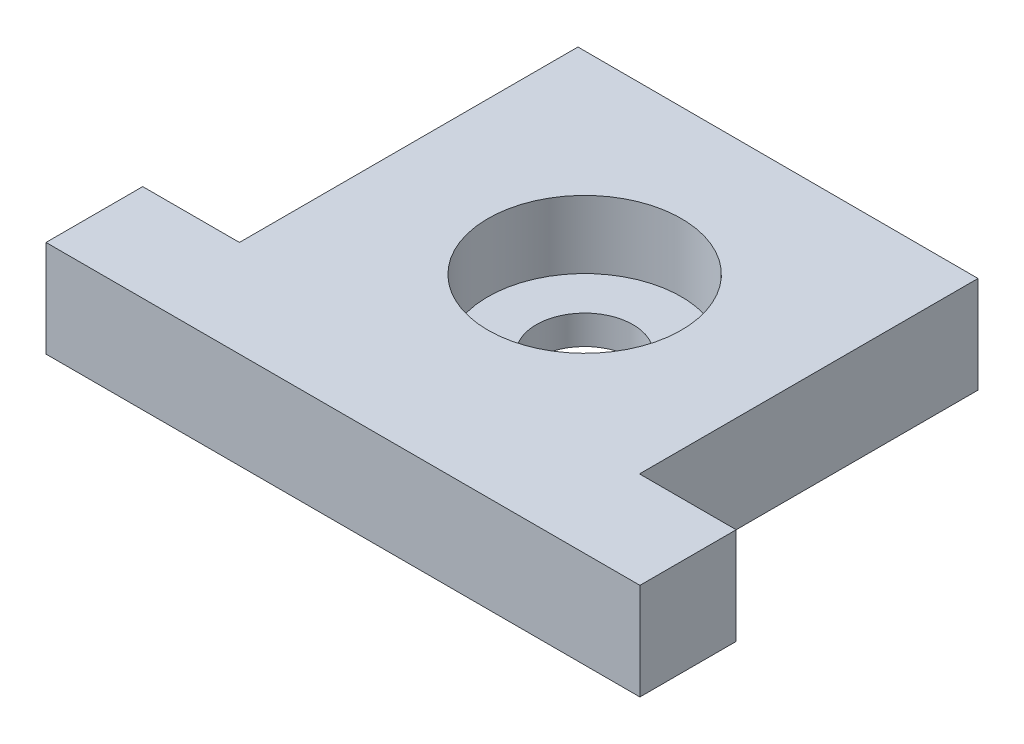
SolidWorks part; units mm, degrees
ref_plane "Front Plane" through (0, 0, 0) normal (0, 0, 1) x (1, 0, 0)
ref_plane "Top Plane" through (0, 0, 0) normal (0, 1, 0) x (1, 0, 0)
ref_plane "Right Plane" through (0, 0, 0) normal (1, 0, 0) x (0, 0, -1)
sketch "Sketch1" plane through (0, 0, 0) normal (0, 1, 0) x (1, 0, 0)
  line L0 (-30.704, 0) -> (30.704, 0)
  line L1 (-30.704, 0) -> (-30.704, 10)
  line L2 (30.704, 0) -> (30.704, 9.955)
  line L3 (-30.704, 10) -> (-20.704, 10)
  line L4 (30.704, 9.955) -> (20.704, 9.955)
  line L5 (-20.704, 10) -> (-20.704, 45)
  line L6 (20.704, 9.955) -> (20.704, 44.955)
  line L7 (-20.704, 45) -> (20.704, 44.955)
  line L8 (20.704, 44.955) -> (20.6896, 45.0291)
  point P4 (0, 0)
extrude "Boss-Extrude1" add sketch "Sketch1" along normal blind 10 contours L7 L5 L3 L1 L0 L2 L4 L6
sketch "Sketch2" plane through (0, 10, 0) normal (0, 1, 0) x (1, 0, 0)
  line L0 (-30.704, 0) -> (30.704, 0) construction
  circle A0 centre (0, 24.9888) radius 10
  point P0 (0, 0)
  point P8 (0, 22.4888)
  point P9 (0, 22.4888)
  dimension "D1" = 24.9888
extrude "Cut-Extrude2" cut sketch "Sketch2" against normal blind 7
sketch "Sketch5" plane through (0, 3, 0) normal (0, 1, 0) x (1, 0, 0)
  circle A0 centre (0, 24.9888) radius 5
extrude "Cut-Extrude3" cut sketch "Sketch5" against normal through all
